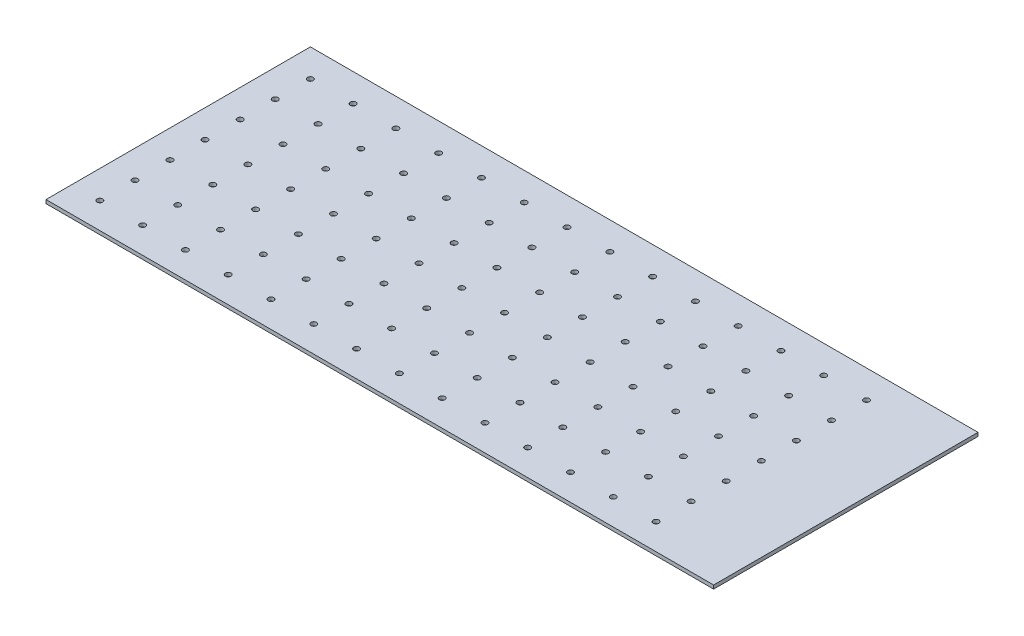
SolidWorks part; units mm, degrees
ref_plane "Front Plane" through (0, 0, 0) normal (0, 0, 1) x (1, 0, 0)
ref_plane "Top Plane" through (0, 0, 0) normal (0, 1, 0) x (1, 0, 0)
ref_plane "Right Plane" through (0, 0, 0) normal (1, 0, 0) x (0, 0, -1)
sketch "Sketch1" plane through (0, 0, 0) normal (0, 1, 0) x (1, 0, 0)
  line L1 (-270, 116.82) -> (270, 116.82)
  line L2 (-270, 116.82) -> (-270, -116.82)
  line L3 (-270, -116.82) -> (270, -116.82)
  line L4 (270, 116.82) -> (270, -116.82)
  line L5 (-270, 116.82) -> (270, -116.82) construction
  line L6 (-270, -116.82) -> (270, 116.82) construction
  point P0 (0, 0)
  dimension "D1" = 540
  dimension "D2" = 233.64
extrude "Boss-Extrude1" add sketch "Sketch1" along normal blind 3.18
sketch "Sketch2" plane through (0, 3.18, 0) normal (0, 1, 0) x (1, 0, 0)
  line L0 (-270, 116.82) -> (-270, -116.82) construction
  line L1 (270, 116.82) -> (-270, 116.82) construction
  circle A0 centre (-245.45, 92.22) radius 2.5
  dimension "D1" = 5
  dimension "D2" = 24.55
  dimension "D3" = 24.6
extrude "Cut-Extrude1" cut sketch "Sketch2" against normal up to next
pattern_linear "LPattern1" count 14 spacing 37.81 along (1, 0, 0) count 7 spacing 31 along (0, 0, 1) of "Cut-Extrude1"
sketch "Sketch3" plane through (270, 0, 0) normal (1, 0, 0) x (0, 0, -1)
  line L1 (-116.82, 3.18) -> (116.82, 3.18)
  line L2 (-116.82, 3.18) -> (-116.82, 0)
  line L3 (-116.82, 0) -> (116.82, 0)
  line L4 (116.82, 3.18) -> (116.82, 0)
extrude "Boss-Extrude2" add sketch "Sketch3" along normal blind 50
